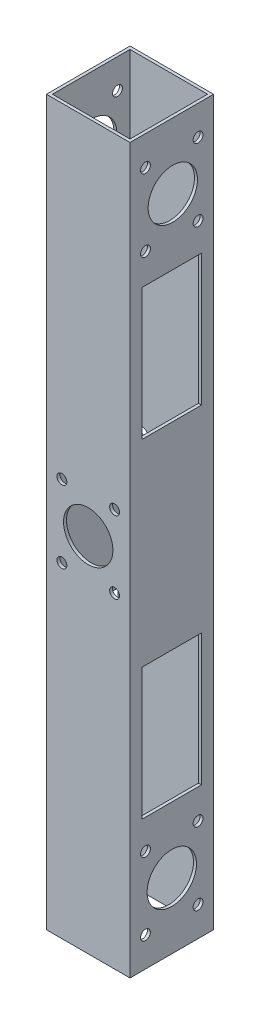
SolidWorks part; units mm, degrees
ref_plane "Front Plane" through (0, 0, 0) normal (0, 0, 1) x (1, 0, 0)
ref_plane "Top Plane" through (0, 0, 0) normal (0, 1, 0) x (1, 0, 0)
ref_plane "Right Plane" through (0, 0, 0) normal (1, 0, 0) x (0, 0, -1)
sketch "Sketch1" plane through (0, 0, 0) normal (0, 1, 0) x (1, 0, 0)
  line L0 (-11.8, 11.8) -> (-11.8, -11.8)
  line L1 (-12.7, 12.7) -> (12.7, 12.7)
  line L2 (-12.7, 12.7) -> (-12.7, -12.7)
  line L3 (-12.7, -12.7) -> (12.7, -12.7)
  line L4 (12.7, 12.7) -> (12.7, -12.7)
  line L5 (-12.7, 12.7) -> (12.7, -12.7) construction
  line L6 (-12.7, -12.7) -> (12.7, 12.7) construction
  line L7 (-11.8, -11.8) -> (11.8, -11.8)
  line L8 (11.8, 11.8) -> (11.8, -11.8)
  line L9 (-11.8, 11.8) -> (11.8, 11.8)
  point P0 (0, 0)
  dimension "D1" = 0.9
extrude "Boss-Extrude1" add sketch "Sketch1" along normal blind 220
sketch "Sketch2" plane through (0, 0, -12.7) normal (0, 0, -1) x (-1, 0, 0)
  circle A0 centre (0, 110) radius 7.5
extrude "Cut-Extrude1" cut sketch "Sketch2" against normal blind 25.4
sketch "Sketch3" plane through (12.7, 0, 0) normal (1, 0, 0) x (0, 0, -1)
  line L3 (-9, 40) -> (9, 40)
  line L4 (-9, 80) -> (9, 80)
  line L5 (9, 180) -> (9, 140)
  line L6 (9, 40) -> (9, 80)
  line L7 (-9, 40) -> (-9, 80)
  line L10 (-9, 180) -> (9, 180)
  line L11 (-9, 180) -> (-9, 140)
  line L12 (-9, 140) -> (9, 140)
  circle A0 centre (0, 20) radius 7.5
  circle A1 centre (0.307, 200) radius 7.5
  point P8 (-12.7, 40)
  point P9 (12.7, 40)
extrude "Cut-Extrude2" cut sketch "Sketch3" against normal blind 25.4
sketch "Sketch4" plane through (-12.7, 0, 0) normal (-1, 0, 0) x (0, 0, 1)
  circle A4 centre (8, 9) radius 1.5
  circle A9 centre (8, 31) radius 1.5
  circle A10 centre (-8, 9) radius 1.5
  circle A11 centre (-8, 31) radius 1.5
  circle A12 centre (8, 211) radius 1.5
  circle A13 centre (-8, 211) radius 1.5
  circle A14 centre (8, 189) radius 1.5
  circle A15 centre (-8, 189) radius 1.5
sketch "Sketch5" plane through (0, 0, -12.7) normal (0, 0, -1) x (-1, 0, 0)
  circle A1 centre (8, 99) radius 1.5
  circle A5 centre (8, 121) radius 1.5
  circle A6 centre (-8, 121) radius 1.5
  circle A7 centre (-8, 99) radius 1.5
extrude "Cut-Extrude4" cut sketch "Sketch5" against normal blind 25.4
extrude "Cut-Extrude5" cut sketch "Sketch4" against normal blind 25.4
